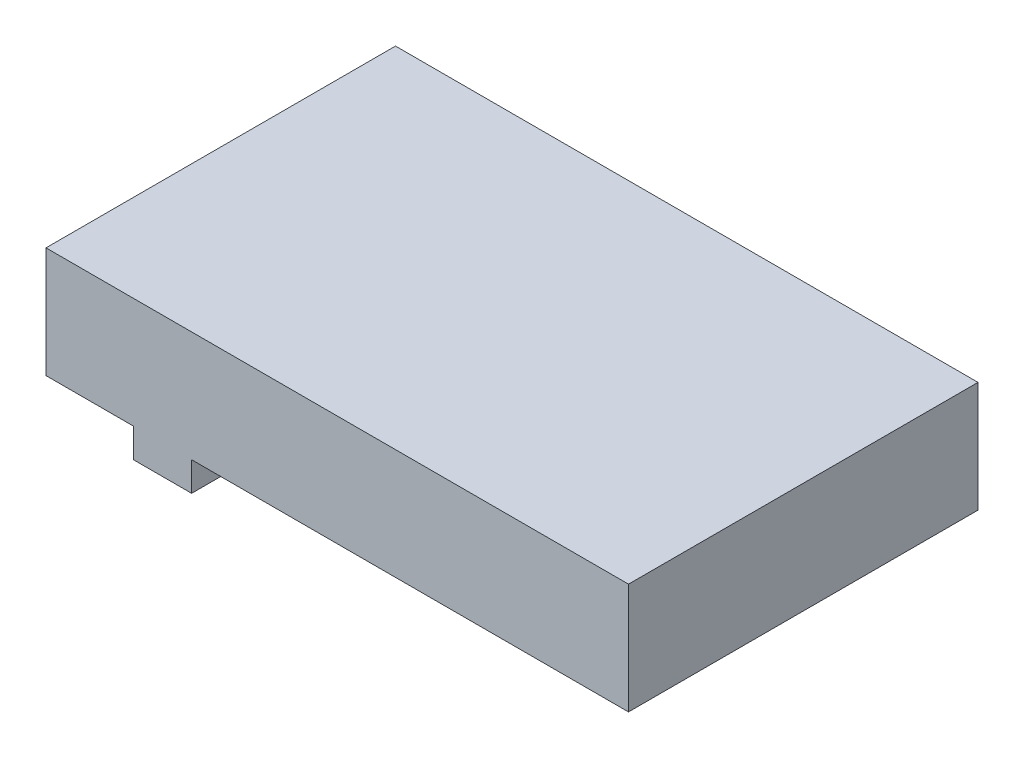
SolidWorks part; units mm, degrees
ref_plane "Front Plane" through (0, 0, 0) normal (0, 0, 1) x (1, 0, 0)
ref_plane "Top Plane" through (0, 0, 0) normal (0, 1, 0) x (1, 0, 0)
ref_plane "Right Plane" through (0, 0, 0) normal (1, 0, 0) x (0, 0, -1)
sketch "Sketch1" plane through (0, 0, 0) normal (0, 0, 1) x (1, 0, 0)
  line L1 (-12.7, -2.413) -> (12.7, -2.413)
  line L2 (-12.7, -2.413) -> (-12.7, 2.413)
  line L3 (-12.7, 2.413) -> (12.7, 2.413)
  line L4 (12.7, -2.413) -> (12.7, 2.413)
  line L5 (-12.7, -2.413) -> (12.7, 2.413) construction
  line L6 (-12.7, 2.413) -> (12.7, -2.413) construction
  point P0 (0, 0)
  dimension "D1" = 4.826
  dimension "D2" = 25.4
extrude "Boss-Extrude1" add sketch "Sketch1" along normal blind 15.24
sketch "Sketch2" plane through (0, 0, 15.24) normal (0, 0, 1) x (1, 0, 0)
  line L0 (-12.7, -2.413) -> (12.7, -2.413) construction
  line L1 (-8.89, -2.413) -> (-6.35, -2.413)
  line L2 (-8.89, -2.413) -> (-8.89, -3.683)
  line L3 (-8.89, -3.683) -> (-6.35, -3.683)
  line L4 (-6.35, -2.413) -> (-6.35, -3.683)
  line L5 (-12.7, 2.413) -> (-12.7, -2.413) construction
  dimension "D1" = 3.81
  dimension "D2" = 1.27
  dimension "D3" = 2.54
extrude "Boss-Extrude2" add sketch "Sketch2" against normal blind 15.24
